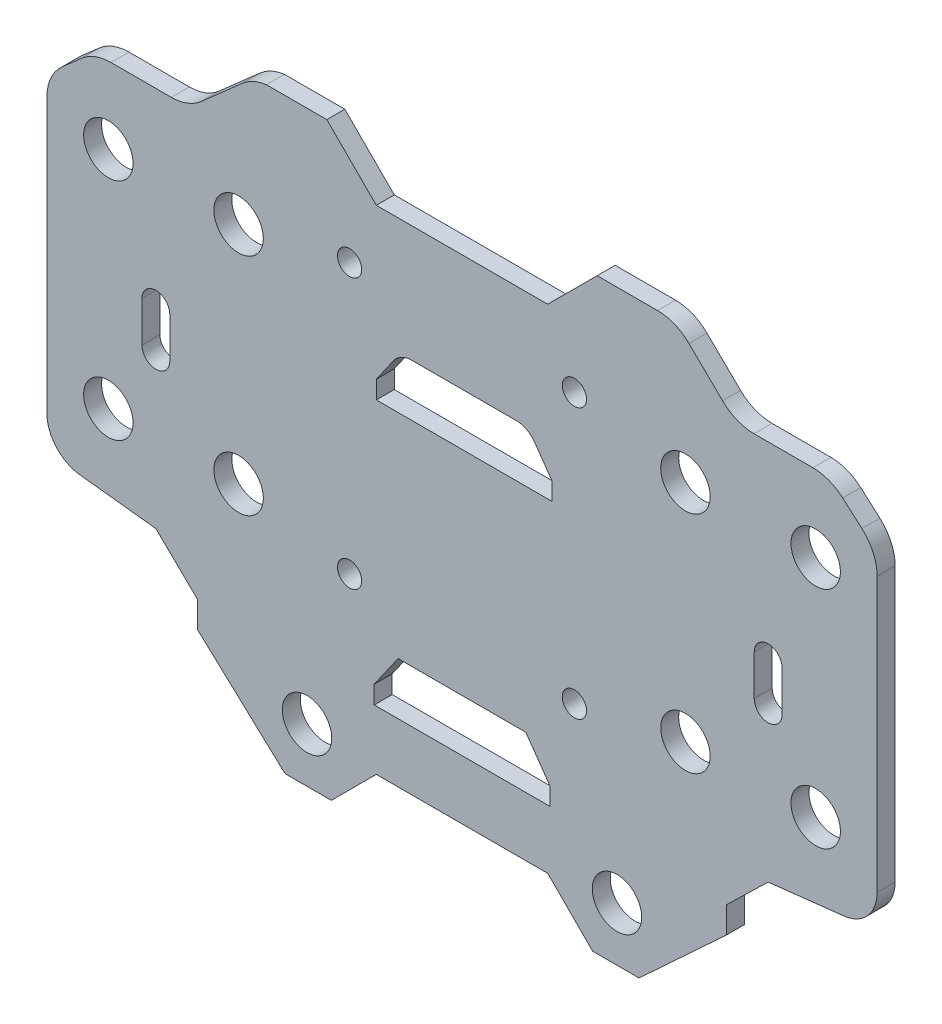
SolidWorks part; units mm, degrees
material "Thornel VCB-20 碳布"
ref_plane "前视基准面" through (0, 0, 0) normal (0, 0, 1) x (1, 0, 0)
ref_plane "上视基准面" through (0, 0, 0) normal (0, 1, 0) x (1, 0, 0)
ref_plane "右视基准面" through (0, 0, 0) normal (1, 0, 0) x (0, 0, -1)
sketch "主结构参考" plane through (0, 0, 0) normal (0, 0, 1) x (1, 0, 0)
  line L257 (0, -1000) -> (0, 49000) construction
  line L346 (0, 0) -> (635.1265, 0) construction
  line L351 (-46.1708, 93.9243) -> (-46.1708, 145) construction
  line L358 (-27.9426, 92.9426) -> (-32.5, 97.5) construction
  line L394 (-24.4478, 142.8678) -> (-29.0158, 138.8343)
  line L411 (-32.3253, 137.5823) -> (-39.0335, 137.5823)
  line L414 (-42.3429, 136.3303) -> (-44.4803, 134.4431)
  line L445 (-46.1708, 130.695) -> (-46.1708, 100.2446)
  line L472 (42.3429, 136.3303) -> (44.4803, 134.4431)
  line L494 (46.1729, 155.4291) -> (33.7932, 145.5483) construction
  line L496 (32.4724, 137.5823) -> (39.0335, 137.5823)
  line L497 (25.2455, 142.6568) -> (28.9763, 139.0078)
  line L498 (27.9426, 92.9426) -> (32.5, 97.5) construction
  line L501 (-46.2756, 154.6927) -> (-33.8959, 144.8119) construction
  line L595 (-39.3354, 129.0823) -> (-39.3354, 104.0823) construction
  line L626 (-31.6538, 83.28) -> (-46.1708, 93.9243) construction
  line L628 (-39.3354, 116.5823) -> (0, 116.5823) construction
  line L629 (-15.0322, 144.0823) -> (-9.5322, 138.5823)
  line L630 (-9.5322, 138.5823) -> (9.5322, 138.5823)
  line L631 (15.0322, 144.0823) -> (9.5322, 138.5823)
  line L633 (-21.7494, 144.0823) -> (-15.0322, 144.0823)
  line L635 (15.0322, 144.0823) -> (21.7494, 144.0823)
  line L641 (-9.5322, 83.7633) -> (9.5322, 83.7633)
  line L643 (-9.5322, 83.7633) -> (-14.5322, 78.7633)
  line L644 (30.4418, 78.7633) -> (14.5322, 78.7633) construction
  line L645 (9.5322, 83.7633) -> (14.5322, 78.7633)
  line L646 (7.1054, 96.1323) -> (-7.1054, 96.1323)
  line L647 (-7.1054, 96.1323) -> (-9.7615, 92.339)
  line L648 (-9.7615, 92.339) -> (-9.7615, 90.339)
  line L649 (-9.7615, 90.339) -> (9.7615, 90.339)
  line L652 (9.7615, 92.339) -> (9.7615, 90.339)
  line L653 (7.1054, 96.1323) -> (9.7615, 92.339)
  line L666 (-35.6, 116.5823) -> (-35.6, 112.0823)
  line L668 (-32.5, 116.5823) -> (-32.5, 112.0823)
  line L670 (35.6, 116.5823) -> (35.6, 112.0823)
  line L671 (32.5, 116.5823) -> (32.5, 112.0823)
  line L672 (6.0333, 125.6256) -> (-5.5747, 125.6256)
  line L673 (-7.6225, 124.5595) -> (-9.5322, 121.8323)
  line L674 (-9.5322, 121.8323) -> (-9.5322, 119.8323)
  line L675 (-9.5322, 119.8323) -> (9.9908, 119.8323)
  line L676 (9.9908, 121.8323) -> (9.9908, 119.8323)
  line L677 (8.0812, 124.5595) -> (9.9908, 121.8323)
  line L681 (-19.6882, 78.7633) -> (-14.5322, 78.7633)
  line L686 (14.5322, 78.7633) -> (19.6882, 78.7633)
  line L687 (-42.4964, 96.1323) -> (-34.05, 95.1793)
  line L688 (-34.05, 95.1793) -> (-29.4424, 90.7125)
  line L691 (-29.4424, 90.7125) -> (-29.4424, 87.7898)
  line L692 (-29.4424, 87.7898) -> (-19.6882, 78.7633)
  line L693 (29.4424, 87.7898) -> (19.6882, 78.7633)
  line L694 (29.4424, 90.7125) -> (29.4424, 87.7898)
  line L695 (34.05, 95.1793) -> (29.4424, 90.7125)
  line L696 (42.4964, 96.1323) -> (34.05, 95.1793)
  line L697 (46.1708, 130.695) -> (46.1708, 100.2446)
  circle A384 centre (39.3354, 129.0823) radius 2.75
  circle A385 centre (39.3354, 104.0823) radius 2.75
  circle A390 centre (17.238, 84.7633) radius 2.75
  circle A420 centre (-17.238, 84.7633) radius 2.75
  circle A421 centre (-39.3354, 104.0823) radius 2.75
  circle A422 centre (-39.3354, 129.0823) radius 2.75
  arc A453 (32.7926, 143.0294) -> (32.5, 97.5) centre (-120.6696, 121.25) cw construction
  arc A454 (-32.8936, 142.3057) -> (-32.5, 97.5) centre (120.6696, 121.25) ccw construction
  arc A455 (-27.9426, 92.9426) -> (27.9426, 92.9426) centre (0, 290.981) ccw construction
  arc A456 (33.7932, 145.5483) -> (32.7926, 143.0294) centre (35.4973, 143.4132) ccw construction
  arc A457 (-32.8936, 142.3057) -> (-33.8959, 144.8119) centre (-35.6, 142.6768) ccw construction
  circle A463 centre (24.85, 129.0823) radius 2.75
  circle A464 centre (-24.85, 129.0823) radius 2.75
  circle A465 centre (-24.85, 104.0823) radius 2.75
  circle A466 centre (24.85, 104.0823) radius 2.75
  circle A467 centre (12.5, 131.5823) radius 1.35
  circle A468 centre (-12.5, 131.5823) radius 1.35
  circle A469 centre (-12.5, 101.5823) radius 1.35
  circle A470 centre (12.5, 101.5823) radius 1.35
  arc A473 (-44.4803, 134.4431) -> (-46.1708, 130.695) centre (-41.1708, 130.695) ccw
  arc A474 (-39.0335, 137.5823) -> (-42.3429, 136.3303) centre (-39.0335, 132.5823) ccw
  arc A475 (46.1708, 130.695) -> (44.4803, 134.4431) centre (41.1708, 130.695) ccw
  arc A476 (42.3429, 136.3303) -> (39.0335, 137.5823) centre (39.0335, 132.5823) ccw
  arc A477 (32.4724, 137.5823) -> (28.9763, 139.0078) centre (32.4724, 142.5823) cw
  arc A478 (-29.0158, 138.8343) -> (-32.3253, 137.5823) centre (-32.3253, 142.5823) cw
  arc A479 (25.2455, 142.6568) -> (21.7494, 144.0823) centre (21.7494, 139.0823) ccw
  arc A480 (-21.7494, 144.0823) -> (-24.4478, 142.8678) centre (-21.1384, 139.1198) ccw
  arc A481 (-35.6, 116.5823) -> (-32.5, 116.5823) centre (-34.05, 116.5823) cw
  arc A484 (-35.6, 112.0823) -> (-32.5, 112.0823) centre (-34.05, 112.0823) ccw
  arc A486 (35.6, 116.5823) -> (32.5, 116.5823) centre (34.05, 116.5823) ccw
  arc A487 (35.6, 112.0823) -> (32.5, 112.0823) centre (34.05, 112.0823) cw
  arc A488 (6.0333, 125.6256) -> (8.0812, 124.5595) centre (6.0333, 123.1256) cw
  arc A489 (-5.5747, 125.6256) -> (-7.6225, 124.5595) centre (-5.5747, 123.1256) ccw
  arc A490 (-46.1708, 100.2446) -> (-42.4964, 96.1323) centre (-42.0324, 100.2446) ccw
  arc A491 (46.1708, 100.2446) -> (42.4964, 96.1323) centre (42.0324, 100.2446) cw
  point P15 (0, 78.5133)
  point P46 (-46.1708, 132.9503)
  point P50 (-40.925, 137.5823)
  point P53 (46.1708, 132.9503)
  point P56 (40.925, 137.5823)
  point P59 (30.4337, 137.5823)
  point P62 (-30.4337, 137.5823)
  point P65 (23.8205, 144.5823)
  point P69 (-23.8205, 144.5823)
  point P76 (0, 138.5823)
  point P90 (0, 90.339)
  point P92 (0, 96.1323)
  point P118 (0.2293, 119.8323)
  point P120 (0.2293, 125.6256)
  dimension "D1" = 84.7633
  dimension "D2" = 17.238
  dimension "D5" = 44.319
  dimension "D6" = 19.319
  dimension "D7" = 22.0974
  dimension "D8" = 22.0974
  dimension "D9" = 6.5
  dimension "D11" = 46.1708
  dimension "D15" = 33.5
  dimension "D17" = 6
  dimension "D23" = 30
  dimension "D38" = 5.5
  dimension "D39" = 155
  dimension "D40" = 200
  dimension "D20" = 5.5
  dimension "D21" = 2.7
  dimension "D22" = 12.5
  dimension "D27" = 135
  dimension "D31" = 1.55
  dimension "D10" = 138.556
  dimension "D12" = 31.6538
  dimension "D13" = 93.9243
  dimension "D14" = 83.28
  dimension "D16" = 5.5
  dimension "D18" = 24.85
  dimension "D19" = 12.5
  dimension "D25" = 5
  dimension "D26" = 135
  dimension "D28" = 125
  dimension "D29" = 2
  dimension "D30" = 20.45
  dimension "D32" = 32.5
  dimension "D33" = 4.5
  dimension "D34" = 3.25
extrude "凸台-拉伸1" add sketch "主结构参考" along normal blind 2
